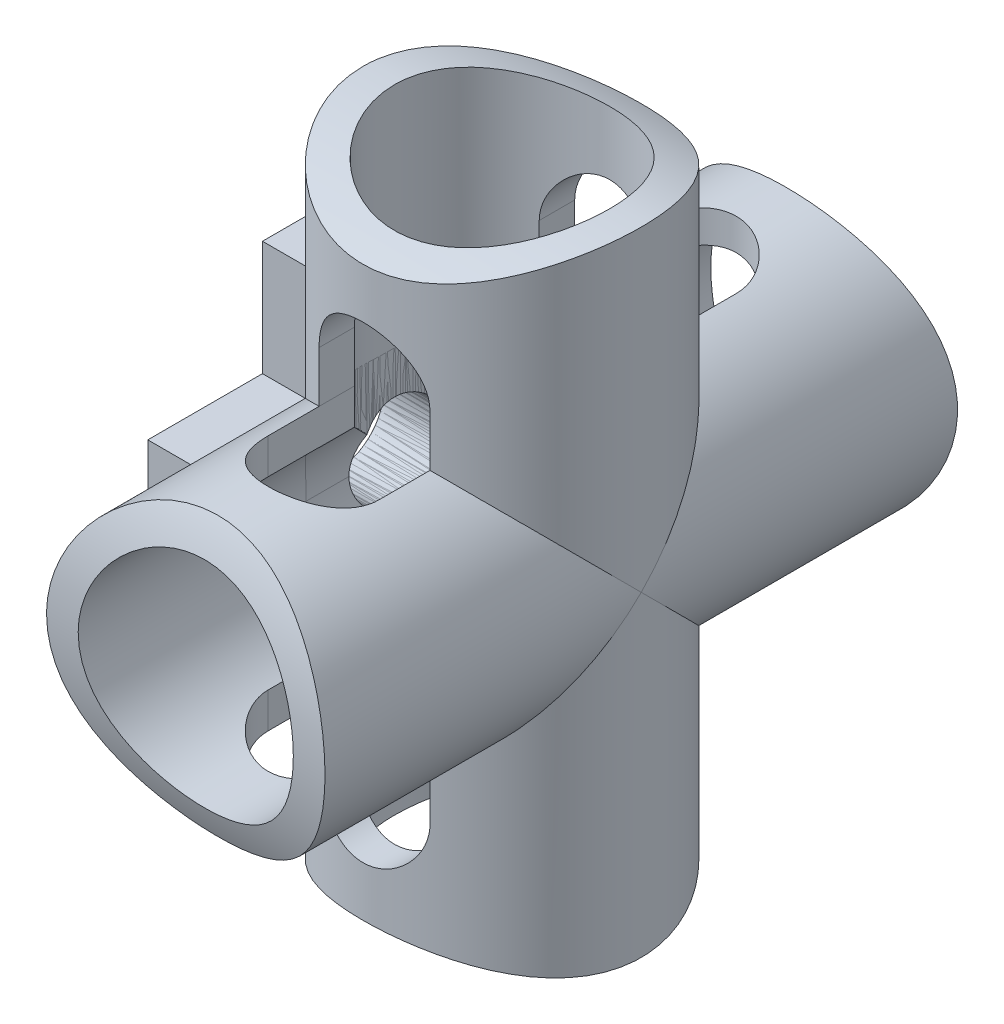
SolidWorks part; units mm, degrees
material "ABS"
ref_plane "Front Plane" through (0, 0, 0) normal (0, 0, 1) x (1, 0, 0)
ref_plane "Top Plane" through (0, 0, 0) normal (0, 1, 0) x (1, 0, 0)
ref_plane "Right Plane" through (0, 0, 0) normal (1, 0, 0) x (0, 0, -1)
sketch "Sketch1" plane through (0, 0, 0) normal (0, 1, 0) x (1, 0, 0)
  circle A0 centre (0, 0) radius 11.176
  circle A1 centre (0, 0) radius 8.636
  dimension "D1" = 22.352
  dimension "D2" = 17.272
extrude "Boss-Extrude1" add sketch "Sketch1" along normal blind 45.72 and the other way blind 2.54
sketch "Sketch2" plane through (0, 45.72, 0) normal (0, 1, 0) x (1, 0, 0)
  circle A0 centre (0, 0) radius 10.668
extrude "Boss-Extrude2" add sketch "Sketch2" against normal blind 2.032
sketch "Sketch3" plane through (0, 0, 0) normal (0, 0, 1) x (1, 0, 0)
  line L0 (55, 0) -> (-55, 0) construction
  line L1 (-0.0152, 24.8919) -> (0.0152, 20.8281) construction
  line L4 (0, 45.72) -> (0, 0) construction
  line L6 (-0.0152, 37.211) -> (-0.0152, 29.3369) construction
  line L7 (4.4298, 37.211) -> (4.4298, 29.3369)
  line L8 (-4.4602, 37.211) -> (-4.4602, 29.3369)
  line L9 (0.0152, 8.509) -> (0.0152, 16.3831) construction
  line L10 (-4.4298, 8.509) -> (-4.4298, 16.3831)
  line L11 (4.4602, 8.509) -> (4.4602, 16.3831)
  line L12 (11.176, 45.72) -> (-11.176, 45.72) construction
  arc A2 (4.4298, 37.211) -> (-4.4602, 37.211) centre (-0.0152, 37.211) ccw
  arc A3 (-4.4602, 29.3369) -> (4.4298, 29.3369) centre (-0.0152, 29.3369) ccw
  arc A4 (-4.4298, 8.509) -> (4.4602, 8.509) centre (0.0152, 8.509) ccw
  arc A5 (4.4602, 16.3831) -> (-4.4298, 16.3831) centre (0.0152, 16.3831) ccw
  point P0 (0.0152, 4.064)
  point P6 (-0.0152, 41.656)
  point P7 (-0.0152, 24.8919)
  point P8 (0.0152, 20.8281)
  point P12 (0, 22.86)
  point P13 (0, 22.86)
  point P18 (-0.0152, 33.274)
  point P25 (0.0152, 12.446)
  dimension "D2" = 4.064
  dimension "D3" = 4.064
  dimension "D4" = 8.89
  dimension "D1" = 4.064
  dimension "D5" = 8.89
extrude "Cut-Extrude1" cut sketch "Sketch3" against normal through all and the other way through all
sketch "Sketch4" plane through (0, 45.72, 0) normal (0, 1, 0) x (1, 0, 0)
  circle A0 centre (0, 0) radius 4.445
  dimension "D1" = 8.89
extrude "Cut-Extrude2" cut sketch "Sketch4" against normal up to next
ref_plane "Plane1" through (-10.668, 0, 0) normal (1, 0, 0) x (0, 0, -1)
sketch "Sketch5" plane through (-10.668, 0, 0) normal (1, 0, 0) x (0, 0, -1)
  line L0 (0, 45.72) -> (0, 0) construction
  line L1 (11.176, 45.72) -> (-11.176, 45.72) construction
  line L2 (0, 22.86) -> (11.176, 0.762) construction
  line L3 (11.176, -2.54) -> (11.176, 4.064) construction
  line L5 (-6.0325, 7.62) -> (6.0325, 7.62)
  line L6 (-6.0325, 7.62) -> (-6.0325, 38.1)
  line L7 (-6.0325, 38.1) -> (6.0325, 38.1)
  line L8 (6.0325, 7.62) -> (6.0325, 38.1)
  line L9 (-6.0325, 7.62) -> (6.0325, 38.1) construction
  line L10 (-6.0325, 38.1) -> (6.0325, 7.62) construction
  dimension "D1" = 30.48
  dimension "D2" = 12.065
extrude "Boss-Extrude3" add sketch "Sketch5" along normal blind 2.032 and the other way blind 2.54
sketch "Sketch6" plane through (-13.208, 0, 0) normal (-1, 0, 0) x (0, 0, 1)
  line L0 (-6.0325, 38.1) -> (6.0325, 7.62) construction
  line L1 (6.0325, 38.1) -> (-6.0325, 7.62) construction
  circle A0 centre (0, 22.86) radius 3.683
  dimension "D1" = 7.366
extrude "Cut-Extrude3" cut sketch "Sketch6" against normal blind 2.286
sketch "Sketch8" plane through (-13.208, 0, 0) normal (-1, 0, 0) x (0, 0, 1)
  line L0 (0, 0) -> (0, -2.5857) construction
  line L2 (-13.8947, -6.7688) -> (13.8947, -6.7688)
  line L3 (-13.8947, -6.7688) -> (-13.8947, 1.5974)
  line L5 (13.8947, -6.7688) -> (13.8947, 1.5974)
  line L6 (-13.8947, -6.7688) -> (13.8947, 1.5974) construction
  line L7 (-13.8947, 1.5974) -> (13.8947, -6.7688) construction
  arc A1 (-13.8947, 1.5974) -> (13.8947, 1.5974) centre (0, 22.86) ccw
  dimension "D2" = 50.8
  dimension "D1" = 2.5857
  dimension "D3" = 8.3662
  dimension "D4" = 27.7894
extrude "Cut-Extrude4" cut sketch "Sketch8" against normal through all
fillet "Fillet1" radius 2.54 1 edges at (0, 45.72, 11.176)
ref_plane "Plane2" through (0, 22.86, 0) normal (0, 1, 0) x (1, 0, 0)
sketch "Sketch13" plane through (0, 22.86, 0) normal (0, 1, 0) x (1, 0, 0)
  line L1 (-18.431, 14.6182) -> (16.3522, 14.6182)
  line L2 (-18.431, 14.6182) -> (-18.431, -13.1737)
  line L3 (-18.431, -13.1737) -> (16.3522, -13.1737)
  line L4 (16.3522, 14.6182) -> (16.3522, -13.1737)
extrude "Cut-Extrude7" cut sketch "Sketch13" along normal through all
pattern_circular "CirPattern2" count 4 over 360 about axis through (0, 22.86, 0) along (1, 0, 0) of bodies 115
sketch "Sketch15" plane through (0, 0, 0) normal (0, 1, 0) x (1, 0, 0)
  circle A0 centre (0, 0) radius 8.636
extrude "Cut-Extrude8" cut sketch "Sketch15" against normal through all and the other way through all
sketch "Sketch16" plane through (-13.208, 0, 0) normal (-1, 0, 0) x (0, 0, 1)
  line L0 (-3.683, 22.86) -> (3.683, 22.86) construction
  circle A0 centre (0, 22.86) radius 3.683
extrude "Cut-Extrude9" cut sketch "Sketch16" against normal up to next (8.7782 mm away)
sketch "Sketch17" plane through (0, 0, 0) normal (0, 0, 1) x (1, 0, 0)
  line L0 (11.176, 22.86) -> (-9.4081, 22.86) construction
  circle A0 centre (0, 22.86) radius 8.6166
extrude "Cut-Extrude10" cut sketch "Sketch17" against normal through all and the other way through all
